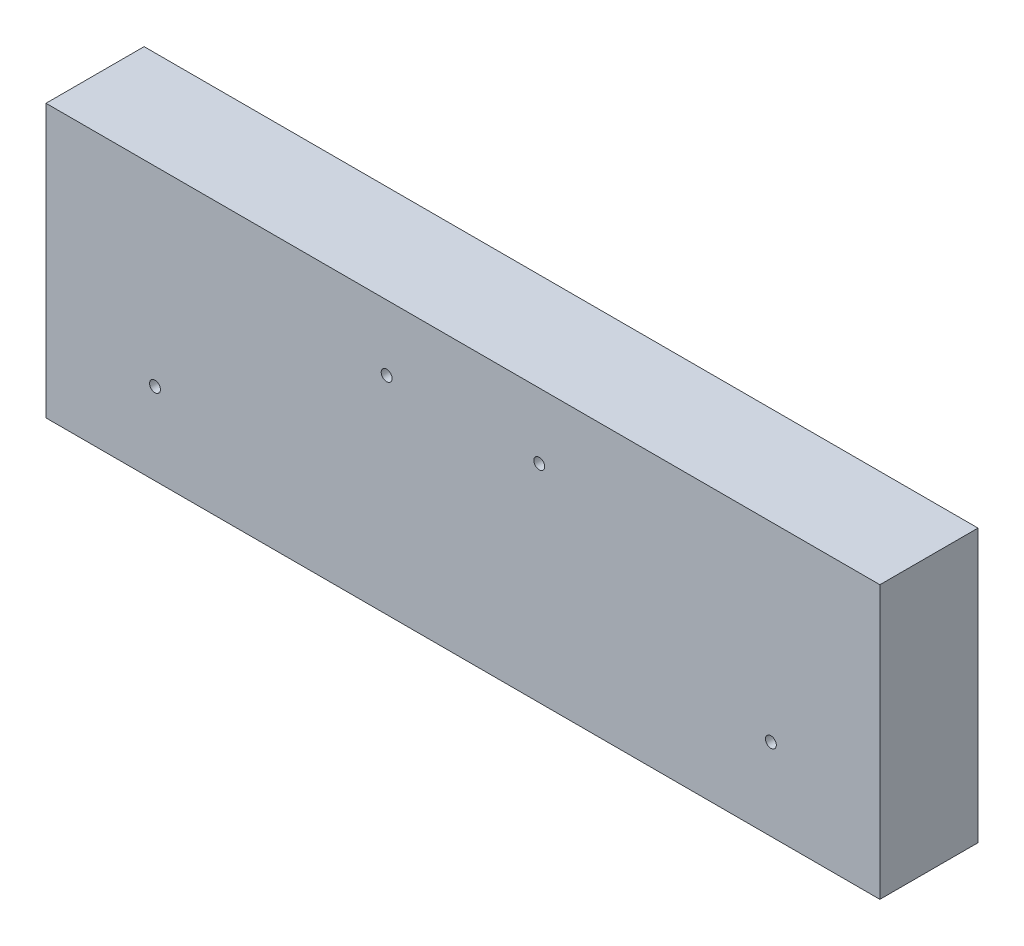
SolidWorks part; units mm, degrees
ref_plane "Front Plane" through (0, 0, 0) normal (0, 0, 1) x (1, 0, 0)
ref_plane "Top Plane" through (0, 0, 0) normal (0, 1, 0) x (1, 0, 0)
ref_plane "Right Plane" through (0, 0, 0) normal (1, 0, 0) x (0, 0, -1)
sketch "Sketch1" plane through (0, 0, 0) normal (0, 0, 1) x (1, 0, 0)
  line L0 (0, 45.315) -> (0, -47.1646) construction
  line L1 (-76.5, 25) -> (76.5, 25)
  line L2 (-76.5, 25) -> (-76.5, -25)
  line L3 (-76.5, -25) -> (76.5, -25)
  line L4 (76.5, 25) -> (76.5, -25)
  line L5 (-14, 41.0467) -> (-14, -27.3882) construction
  line L6 (14, 41.0467) -> (14, -27.3882) construction
  line L7 (-62.8862, 13) -> (40.242, 13) construction
  line L8 (-79.1057, 0) -> (82.6626, 0) construction
  line L9 (56.5, 35.2808) -> (56.5, -38.6838) construction
  line L10 (27.8412, -10) -> (79.4963, -10) construction
  line L11 (-56.5, 33.0185) -> (-56.5, -41.0794) construction
  line L12 (-100.2169, -10) -> (-49.5183, -10) construction
  circle A0 centre (-14, 13) radius 1
  circle A1 centre (14, 13) radius 1
  circle A2 centre (-56.5, -10) radius 1
  circle A3 centre (56.5, -10) radius 1
  dimension "D7" = 2
  dimension "D8" = 20
  dimension "D10" = 20
  dimension "D1" = 153
  dimension "D2" = 50
  dimension "D3" = 14
  dimension "D4" = 14
  dimension "D5" = 12
  dimension "D6" = 15
  dimension "D9" = 15
extrude "Boss-Extrude1" add sketch "Sketch1" along normal blind 18
